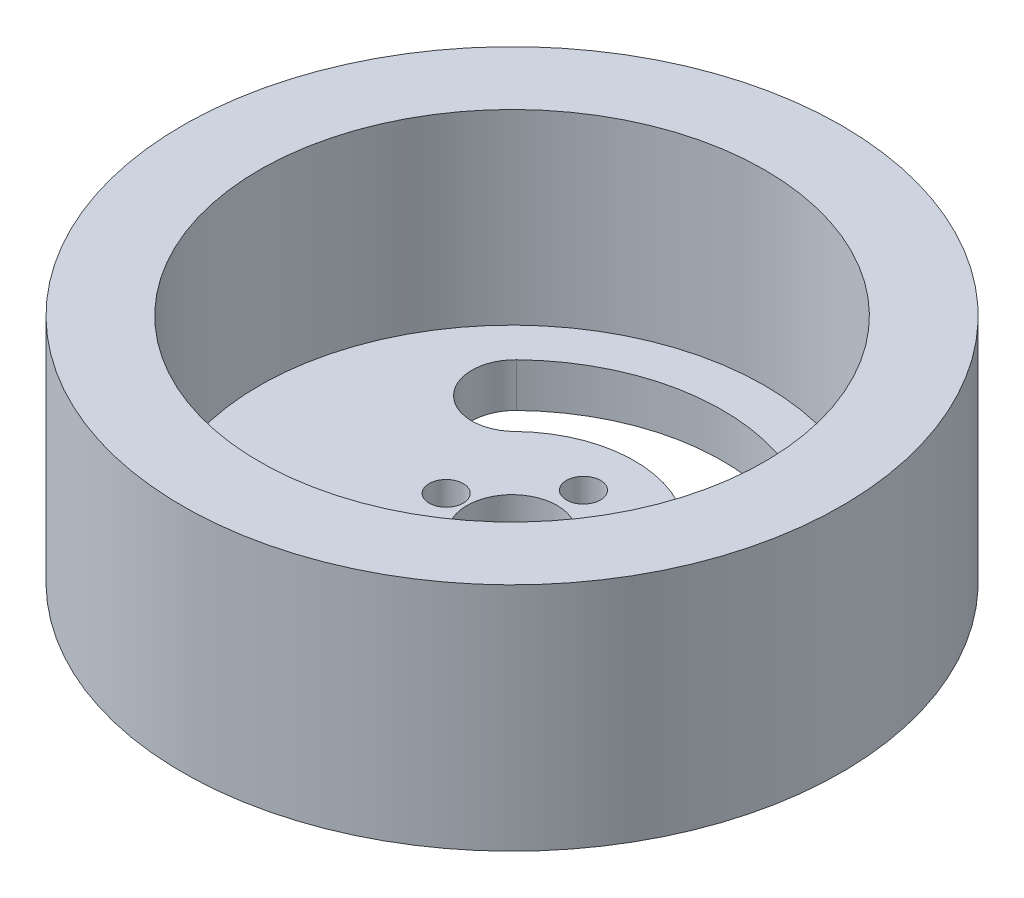
SolidWorks part; units mm, degrees
material "硅橡胶"
ref_plane "前视基准面" through (0, 0, 0) normal (0, 0, 1) x (1, 0, 0)
ref_plane "上视基准面" through (0, 0, 0) normal (0, 1, 0) x (1, 0, 0)
ref_plane "右视基准面" through (0, 0, 0) normal (1, 0, 0) x (0, 0, -1)
sketch "草图1" plane through (0, 0, 0) normal (0, 1, 0) x (1, 0, 0)
  circle A0 centre (0, 0) radius 30
  circle A1 centre (0, 0) radius 23
  dimension "D1" = 46
  dimension "D2" = 60
extrude "凸台-拉伸1" add sketch "草图1" along normal blind 21
sketch "草图2" plane through (0, 0, 0) normal (0, -1, 0) x (1, 0, 0)
  line L0 (55, 0) -> (-55, 0) construction
  circle A0 centre (0, 0) radius 23
  arc A1 (-10.5407, 10.8727) -> (10.8727, 10.5407) centre (0, 0) cw construction
  arc A2 (13.7447, 13.325) -> (-13.325, 13.7447) centre (0, 0) ccw
  arc A3 (8.0008, 7.7565) -> (-7.7565, 8.0008) centre (0, 0) ccw
  arc A4 (8.0008, 7.7565) -> (13.7447, 13.325) centre (10.8727, 10.5407) ccw
  arc A5 (-13.325, 13.7447) -> (-7.7565, 8.0008) centre (-10.5407, 10.8727) ccw
  arc A6 (-10.5407, -10.8727) -> (10.8727, -10.5407) centre (0, 0) ccw construction
  arc A7 (13.7447, -13.325) -> (-13.325, -13.7447) centre (0, 0) cw
  arc A8 (8.0008, -7.7565) -> (-7.7565, -8.0008) centre (0, 0) cw
  arc A9 (8.0008, -7.7565) -> (13.7447, -13.325) centre (10.8727, -10.5407) cw
  arc A10 (-13.325, -13.7447) -> (-7.7565, -8.0008) centre (-10.5407, -10.8727) cw
  circle A11 centre (0, 0) radius 4.1
  circle A12 centre (6, 0) radius 1.55
  circle A13 centre (-6, 0) radius 1.55
  circle A14 centre (0, 6.5) radius 1.55
  circle A15 centre (0, -6.5) radius 1.55
  point P5 (0.2348, 15.1416)
  point P14 (0.2348, -15.1416)
  dimension "D1" = 6
  dimension "D2" = 6
  dimension "D3" = 6.5
  dimension "D4" = 6.5
extrude "凸台-拉伸2" add sketch "草图2" against normal blind 4
